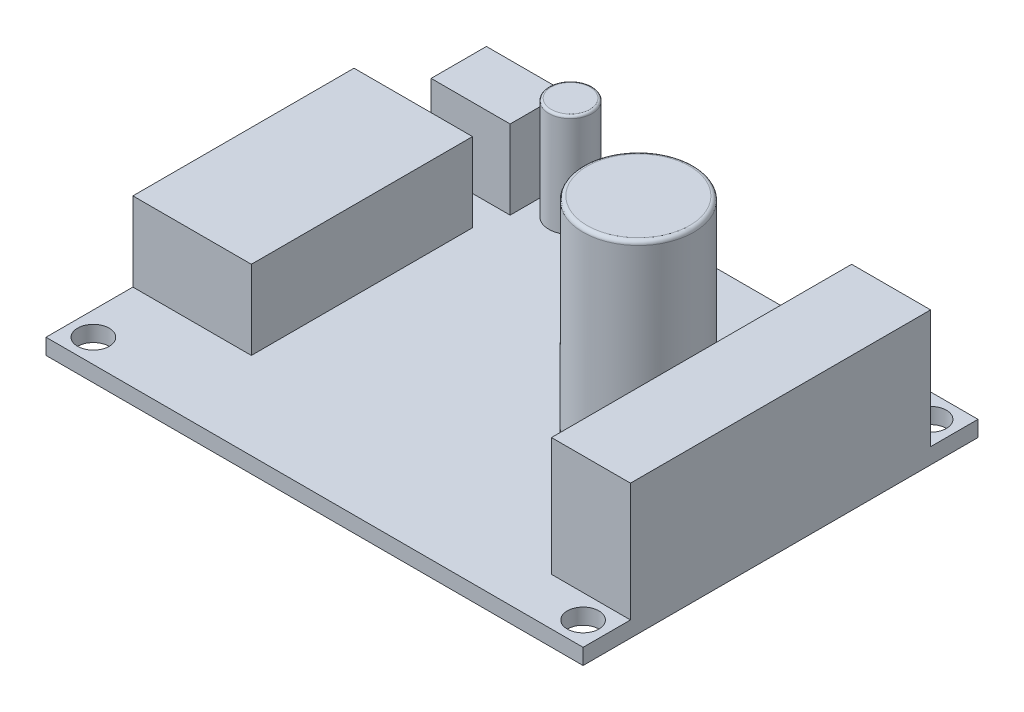
SolidWorks part; units mm, degrees
ref_plane "Front Plane" through (0, 0, 0) normal (0, 0, 1) x (1, 0, 0)
ref_plane "Top Plane" through (0, 0, 0) normal (0, 1, 0) x (1, 0, 0)
ref_plane "Right Plane" through (0, 0, 0) normal (1, 0, 0) x (0, 0, -1)
sketch "Sketch1" plane through (0, 0, 0) normal (0, 1, 0) x (1, 0, 0)
  line L1 (-34, -25) -> (34, -25)
  line L2 (-34, -25) -> (-34, 25)
  line L3 (-34, 25) -> (34, 25)
  line L4 (34, -25) -> (34, 25)
  line L5 (-34, -25) -> (34, 25) construction
  line L6 (-34, 25) -> (34, -25) construction
  circle A0 centre (-31, 22) radius 2
  circle A1 centre (31, 22) radius 2
  circle A2 centre (31, -22) radius 2
  circle A3 centre (-31, -22) radius 2
  point P0 (0, 0)
  dimension "D3" = 4
  dimension "D1" = 68
  dimension "D2" = 50
extrude "Boss-Extrude2" add sketch "Sketch1" along normal blind 2
sketch "Sketch2" plane through (0, 2, 0) normal (0, 1, 0) x (1, 0, 0)
  line L0 (34, -25) -> (34, 25) construction
  circle A0 centre (16, 0) radius 7
  dimension "D1" = 14
  dimension "D2" = 18
extrude "Boss-Extrude3" add sketch "Sketch2" along normal blind 28
fillet "Fillet1" radius 0.5 1 edges at (16, 30, 7)
sketch "Sketch3" plane through (0, 2, 0) normal (0, 1, 0) x (1, 0, 0)
  line L0 (34, -25) -> (34, 25) construction
  line L2 (24, -19) -> (24, 19)
  line L4 (34, -19) -> (34, 19)
  line L5 (61.9749, -16.3579) -> (71.9749, 23.6421) construction
  line L6 (61.9749, 23.6421) -> (71.9749, -16.3579) construction
  line L8 (24, 19) -> (34, 19)
  line L9 (24, -19) -> (34, -19)
  point P0 (66.9749, 3.6421)
  point P5 (34, 0)
  point P6 (34, 0)
extrude "Boss-Extrude4" add sketch "Sketch3" along normal blind 15
sketch "Sketch4" plane through (0, 2, 0) normal (0, 1, 0) x (1, 0, 0)
  line L0 (-34, 25) -> (-34, -25) construction
  line L1 (-34, -14) -> (-19, -14)
  line L2 (-34, -14) -> (-34, 14)
  line L3 (-34, 14) -> (-19, 14)
  line L4 (-19, -14) -> (-19, 14)
  point P5 (-34, 0)
  point P6 (-34, 0)
  dimension "D1" = 28
  dimension "D2" = 15
extrude "Boss-Extrude5" add sketch "Sketch4" along normal blind 10
sketch "Sketch5" plane through (0, 2, 0) normal (0, 1, 0) x (1, 0, 0)
  line L1 (-28.0015, 17.7629) -> (-18.0015, 17.7629)
  line L2 (-28.0015, 17.7629) -> (-28.0015, 24.7629)
  line L3 (-28.0015, 24.7629) -> (-18.0015, 24.7629)
  line L4 (-18.0015, 17.7629) -> (-18.0015, 24.7629)
extrude "Boss-Extrude6" add sketch "Sketch5" along normal blind 10
sketch "Sketch6" plane through (0, 2, 0) normal (0, 1, 0) x (1, 0, 0)
  line L0 (-34, 25) -> (-34, 14) construction
  circle A0 centre (-14, 21.4114) radius 2.75
  dimension "D1" = 5.5
  dimension "D2" = 20
extrude "Boss-Extrude7" add sketch "Sketch6" along normal blind 13
fillet "Fillet2" radius 0.3 1 edges at (-14, 15, -18.6614)
